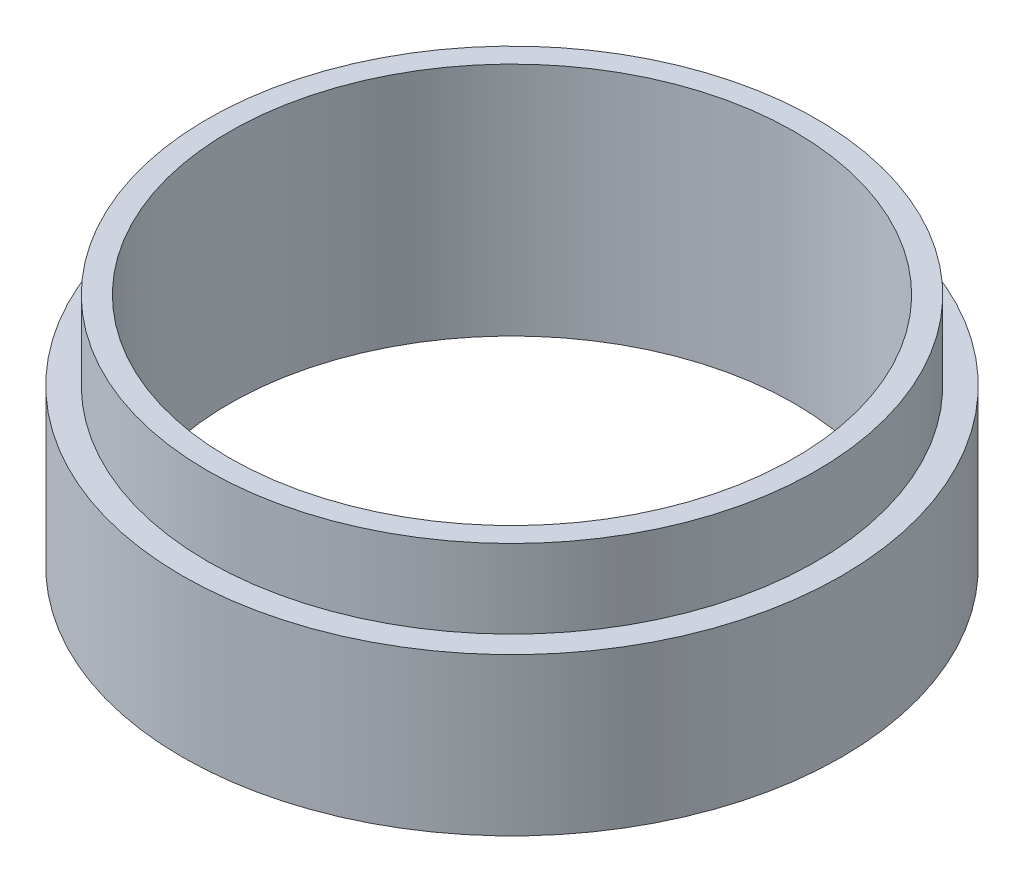
SolidWorks part; units mm, degrees
ref_plane "Front Plane" through (0, 0, 0) normal (0, 0, 1) x (1, 0, 0)
ref_plane "Top Plane" through (0, 0, 0) normal (0, 1, 0) x (1, 0, 0)
ref_plane "Right Plane" through (0, 0, 0) normal (1, 0, 0) x (0, 0, -1)
sketch "Sketch1" plane through (0, 0, 0) normal (0, 0, 1) x (1, 0, 0)
  line L0 (0, 0) -> (0, 23374.4256) construction
  line L1 (0, 0) -> (23374.4256, 0) construction
  line L3 (0, 10) -> (21, 10)
  line L4 (0, 10) -> (0, 0)
  line L5 (0, 0) -> (21, 0)
  line L6 (21, 10) -> (21, 0)
  line L7 (0, 10) -> (21, 0) construction
  line L8 (0, 0) -> (21, 10) construction
  point P5 (10.5, 5)
  dimension "D1" = 42
  dimension "D2" = 10
revolve "Revolve1" add sketch "Sketch1" angle 360 about L0
sketch "Sketch2" plane through (0, 10, 0) normal (0, 1, 0) x (1, 0, 0)
  circle A2 centre (0, 0) radius 18
  circle A3 centre (0, 0) radius 18
  dimension "D1" = 3
extrude "Cut-Extrude1" cut sketch "Sketch2" against normal through all
sketch "Sketch4" plane through (0, 10, 0) normal (0, 1, 0) x (1, 0, 0)
  circle A3 centre (0, 0) radius 19.4
  circle A4 centre (0, 0) radius 19.4
  dimension "D1" = 1.4
extrude "Boss-Extrude1" add sketch "Sketch4" along normal blind 5
sketch "Sketch5" plane through (0, 15, 0) normal (0, 1, 0) x (1, 0, 0)
  circle A2 centre (0, 0) radius 18
  circle A3 centre (0, 0) radius 18
  dimension "D1" = 3
extrude "Cut-Extrude2" cut sketch "Sketch5" against normal through all
